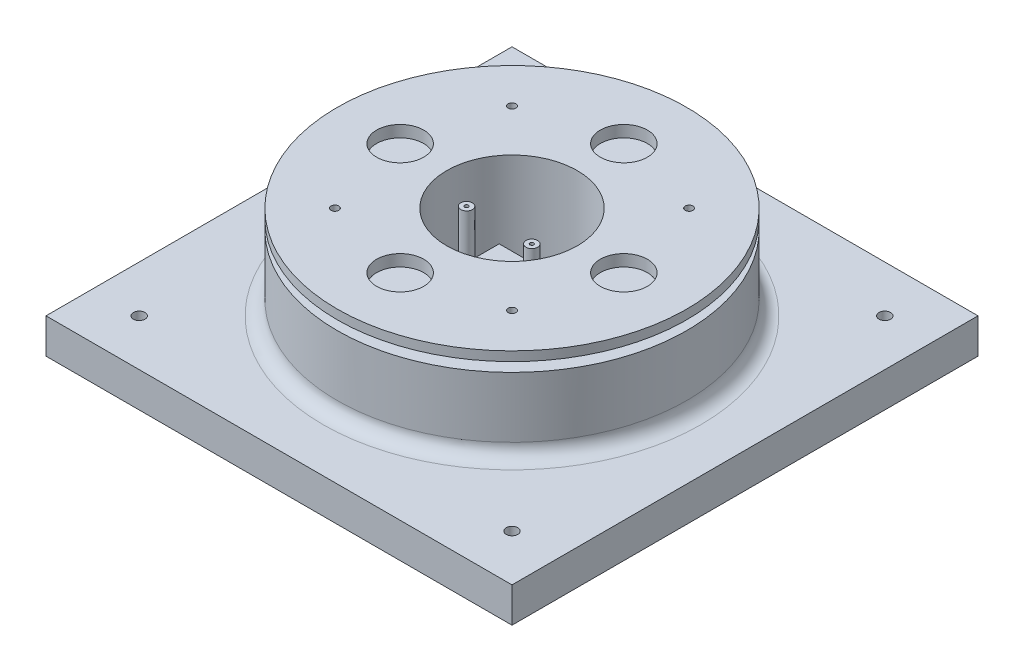
SolidWorks part; units mm, degrees
ref_plane "Front Plane" through (0, 0, 0) normal (0, 0, 1) x (1, 0, 0)
ref_plane "Top Plane" through (0, 0, 0) normal (0, 1, 0) x (1, 0, 0)
ref_plane "Right Plane" through (0, 0, 0) normal (1, 0, 0) x (0, 0, -1)
sketch "Sketch1" plane through (0, 0, 0) normal (0, 1, 0) x (1, 0, 0)
  line L1 (0, 0) -> (200, 0)
  line L2 (0, 0) -> (0, 200)
  line L3 (0, 200) -> (200, 200)
  line L4 (200, 0) -> (200, 200)
  dimension "D1" = 200
  dimension "D2" = 200
extrude "Boss-Extrude1" add sketch "Sketch1" along normal blind 15
sketch "Sketch2" plane through (0, 15, 0) normal (0, 1, 0) x (1, 0, 0)
  line L0 (200, 200) -> (0, 200) construction
  line L2 (0, 200) -> (0, 0) construction
  circle A0 centre (80.5, 100) radius 2.5
  dimension "D3" = 5
  dimension "D1" = 100
  dimension "D2" = 80.5
extrude "Boss-Extrude2" add sketch "Sketch2" along normal blind 31
sketch "Sketch4" plane through (0, 15, 0) normal (0, 1, 0) x (1, 0, 0)
  line L0 (0, 200) -> (0, 0) construction
  line L1 (80.5, 86) -> (108.5, 86)
  line L2 (80.5, 86) -> (80.5, 114)
  line L3 (80.5, 114) -> (108.5, 114)
  line L4 (108.5, 86) -> (108.5, 114)
  line L5 (200, 0) -> (200, 200) construction
  line L6 (0, 0) -> (200, 0) construction
  line L7 (200, 200) -> (0, 200) construction
  dimension "D1" = 80.5
  dimension "D2" = 91.5
  dimension "D3" = 86
  dimension "D4" = 86
extrude "Boss-Extrude3" add sketch "Sketch4" along normal blind 10
pattern_linear "LPattern2" count 2 spacing 28 along (1, 0, 0) of "Boss-Extrude2"
fillet "Fillet1" radius 4 8 edges at (108.5, 15, -91.75) (111, 15, -100) (108.5, 15, -108.25) (94.5, 15, -114) (80.5, 15, -108.25) (78, 15, -100) (80.5, 15, -91.75) (94.5, 15, -86)
sketch "Sketch8" plane through (0, 15, 0) normal (0, 1, 0) x (1, 0, 0)
  line L0 (0, 0) -> (200, 200) construction
  circle A0 centre (100, 100) radius 28
  circle A1 centre (100, 100) radius 75
  dimension "D1" = 56
  dimension "D2" = 150
extrude "Boss-Extrude5" add sketch "Sketch8" along normal blind 32
fillet "Fillet2" radius 6 1 edges at (100, 15, -175)
sketch "Sketch10" plane through (0, 47, 0) normal (0, 1, 0) x (1, 0, 0)
  circle A0 centre (100, 100) radius 28
  circle A1 centre (100, 100) radius 67
  circle A2 centre (100, 100) radius 75 construction
  dimension "D1" = 8
extrude "Boss-Extrude6" add sketch "Sketch10" along normal blind 4
sketch "Sketch11" plane through (0, 51, 0) normal (0, 1, 0) x (1, 0, 0)
  circle A0 centre (100, 100) radius 28
  circle A1 centre (100, 100) radius 75
extrude "Boss-Extrude7" add sketch "Sketch11" along normal blind 4
sketch "Sketch9" plane through (0, 47, 0) normal (0, 1, 0) x (1, 0, 0)
  line L0 (200, 0) -> (200, 200) construction
  line L1 (200, 200) -> (0, 200) construction
  circle A0 centre (100, 148) radius 10.1
  dimension "D3" = 20.2
  dimension "D1" = 100
  dimension "D2" = 52
extrude "Cut-Extrude2" cut sketch "Sketch9" along normal through all
pattern_circular "CirPattern1" count 4 over 360 about axis through (100, 0, -100) along (0, 1, 0) of "Cut-Extrude2"
sketch "Sketch12" plane through (0, 47, 0) normal (0, 1, 0) x (1, 0, 0)
  circle A0 centre (100, 148) radius 10.1
extrude "Boss-Extrude8" add sketch "Sketch12" along normal blind 3
pattern_circular "CirPattern2" count 4 over 360 of "Boss-Extrude8"
hole_wizard "Tap Drill for M6x1.0 Tap1" positions "Sketch18" profile "Sketch19" hole size "M6x1.0" standard "ANSI Metric" end condition up to next
sketch "Sketch18" plane through (0, 15, 0) normal (0, 1, 0) x (1, 0, 0)
  line L0 (0, 200) -> (0, 0) construction
  line L1 (0, 0) -> (200, 0) construction
  point P0 (20, 20)
  dimension "D1" = 20
  dimension "D2" = 20
sketch "Sketch19" plane through (20, 15, -20) normal (1, 0, 0) x (0, 0, 1)
  line L0 (0, 0) -> (0, 15.001)
  line L1 (0, 15.001) -> (2.5, 15.001)
  line L2 (2.5, 15.001) -> (2.5, 0)
  line L5 (2.5, 0) -> (0, 0)
  line L11 (0, -6.35) -> (0, 107.95) construction
  dimension "Thru Hole Dia." = 5
  dimension "Thru Hole Depth" = 15.001
pattern_circular "CirPattern4" count 4 over 360 about axis through (100, 0, -100) along (0, 1, 0) of "Tap Drill for M6x1.0 Tap1"
hole_wizard "Tap Drill for M4x0.7 Tap2" positions "Sketch22" profile "Sketch23" hole size "M4x0.7" standard "ANSI Metric"
sketch "Sketch22" plane through (0, 55, 0) normal (0, 1, 0) x (1, 0, 0)
  circle A0 centre (100, 148) radius 10.1 construction
  circle A1 centre (148, 100) radius 10.1 construction
  point P0 (138, 138)
  dimension "D1" = 10
  dimension "D2" = 10
sketch "Sketch23" plane through (138, 55, -138) normal (1, 0, 0) x (0, 0, 1)
  line L0 (0, 0) -> (0, 20.9914)
  line L1 (0, 20.9914) -> (1.65, 20)
  line L2 (1.65, 20) -> (1.65, 0)
  line L5 (1.65, 0) -> (0, 0)
  line L10 (0, 20.9914) -> (-1.65, 20) construction
  line L11 (0, -6.35) -> (0, 107.95) construction
  dimension "Hole Dia." = 3.3
  dimension "Hole Depth" = 20
  dimension "Drill Angle" = 118
pattern_circular "CirPattern5" count 4 over 360 about axis through (100, 0, -100) along (0, 1, 0) of "Tap Drill for M4x0.7 Tap2"
hole_wizard "Tap Drill for M2x0.4 Tap1" positions "Sketch26" profile "Sketch28" hole size "M2x0.4" standard "ANSI Metric"
sketch "Sketch26" plane through (0, 46, 0) normal (0, 1, 0) x (1, 0, 0)
  circle A0 centre (80.5, 100) radius 2.5 construction
  point P0 (80.5, 100)
  dimension "D1" = 0
sketch "Sketch28" plane through (80.5, 46, -100) normal (1, 0, 0) x (0, 0, 1)
  line L0 (0, 0) -> (0, 10.4807)
  line L1 (0, 10.4807) -> (0.8, 10)
  line L2 (0.8, 10) -> (0.8, 0)
  line L5 (0.8, 0) -> (0, 0)
  line L10 (0, 10.4807) -> (-0.8, 10) construction
  line L11 (0, -6.35) -> (0, 107.95) construction
  dimension "Hole Dia." = 1.6
  dimension "Hole Depth" = 10
  dimension "Drill Angle" = 118
pattern_linear "LPattern3" count 2 spacing 28 along (1, 0, 0) of "Tap Drill for M2x0.4 Tap1"
